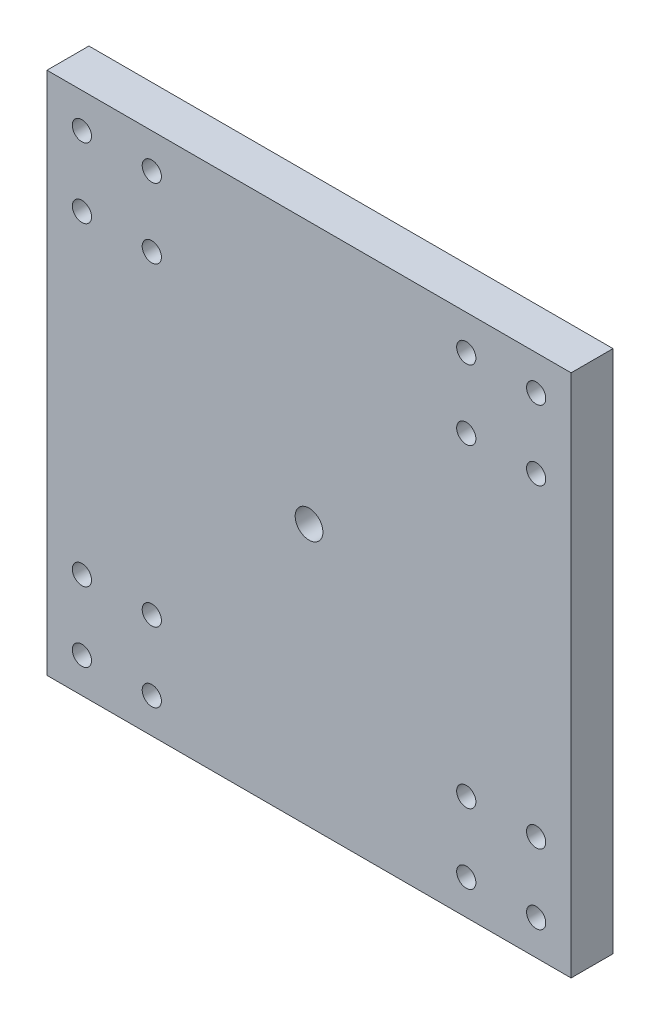
SolidWorks part; units mm, degrees
material "ALUMINIUM,  6082-T6"
ref_plane "Front Plane" through (0, 0, 0) normal (0, 0, 1) x (1, 0, 0)
ref_plane "Top Plane" through (0, 0, 0) normal (0, 1, 0) x (1, 0, 0)
ref_plane "Right Plane" through (0, 0, 0) normal (1, 0, 0) x (0, 0, -1)
sketch "Sketch1" plane through (0, 0, 0) normal (0, 0, 1) x (1, 0, 0)
  line L0 (-75, 75) -> (75, -75) construction
  line L1 (-75, 75) -> (75, 75)
  line L2 (-75, 75) -> (-75, -75)
  line L3 (-75, -75) -> (75, -75)
  line L4 (75, 75) -> (75, -75)
  dimension "D1" = 150
extrude "Boss-Extrude1" add sketch "Sketch1" along normal blind 12
hole_wizard "3/8-16 Tapped Hole1" positions "Sketch2" profile "Sketch3" tap size "3/8-16" standard "ANSI Inch" end condition through all
sketch "Sketch2" plane through (0, 0, 12) normal (0, 0, 1) x (1, 0, 0)
  point P0 (0, 0)
sketch "Sketch3" plane through (0, 0, 12) normal (1, 0, 0) x (0, -1, 0)
  line L0 (0, 0) -> (0, 12)
  line L1 (0, 12) -> (3.9687, 12)
  line L2 (3.9687, 12) -> (3.9687, 0)
  line L5 (3.9687, 0) -> (0, 0)
  line L11 (0, -6.35) -> (0, 107.95) construction
  dimension "Thru Tap Drill Dia." = 7.9375
  dimension "Thru Tap Drill Depth" = 12
cosmetic thread "Hole Thread2" parameters "D2"=9.525
hole_wizard "CBORE for M5 Hex Socket Head Cap Screw1" positions "Sketch4" profile "Sketch5" counterbore size "M5" standard "ISO" end condition through all
sketch "Sketch4" plane through (0, 0, 0) normal (0, 0, 1) x (1, 0, 0)
  point P0 (-65, 65)
  point P2 (-45, 65)
  point P6 (-65, 45)
  point P18 (-65, -45)
  point P20 (-45, -65)
  point P21 (-65, -65)
  point P24 (65, -45)
  point P25 (65, -65)
  point P26 (45, -65)
  point P28 (45, 65)
  point P29 (65, 65)
  point P30 (65, 45)
  point P43 (-45, 45)
  point P45 (45, 45)
  point P47 (45, -45)
  point P49 (-45, -45)
  dimension "D1" = 20
  dimension "D2" = 20
  dimension "D3" = 45
  dimension "D4" = 45
  dimension "D5" = 45
  dimension "D6" = 20
  dimension "D7" = 45
  dimension "D8" = 20
sketch "Sketch5" plane through (-65, 65, 0) normal (1, 0, 0) x (0, 1, 0)
  line L0 (0, 0) -> (0, 12)
  line L1 (0, 12) -> (2.75, 12)
  line L3 (2.75, 12) -> (2.75, 5.5)
  line L4 (2.75, 5.5) -> (5, 5.5)
  line L5 (5, 5.5) -> (5, 0)
  line L7 (5, 0) -> (0, 0)
  line L11 (0, -6.35) -> (0, 107.95) construction
  dimension "Thru Hole Dia." = 5.5
  dimension "Thru Hole Depth" = 12
  dimension "C'Bore Dia." = 10
  dimension "C'Bore Depth" = 5.5
